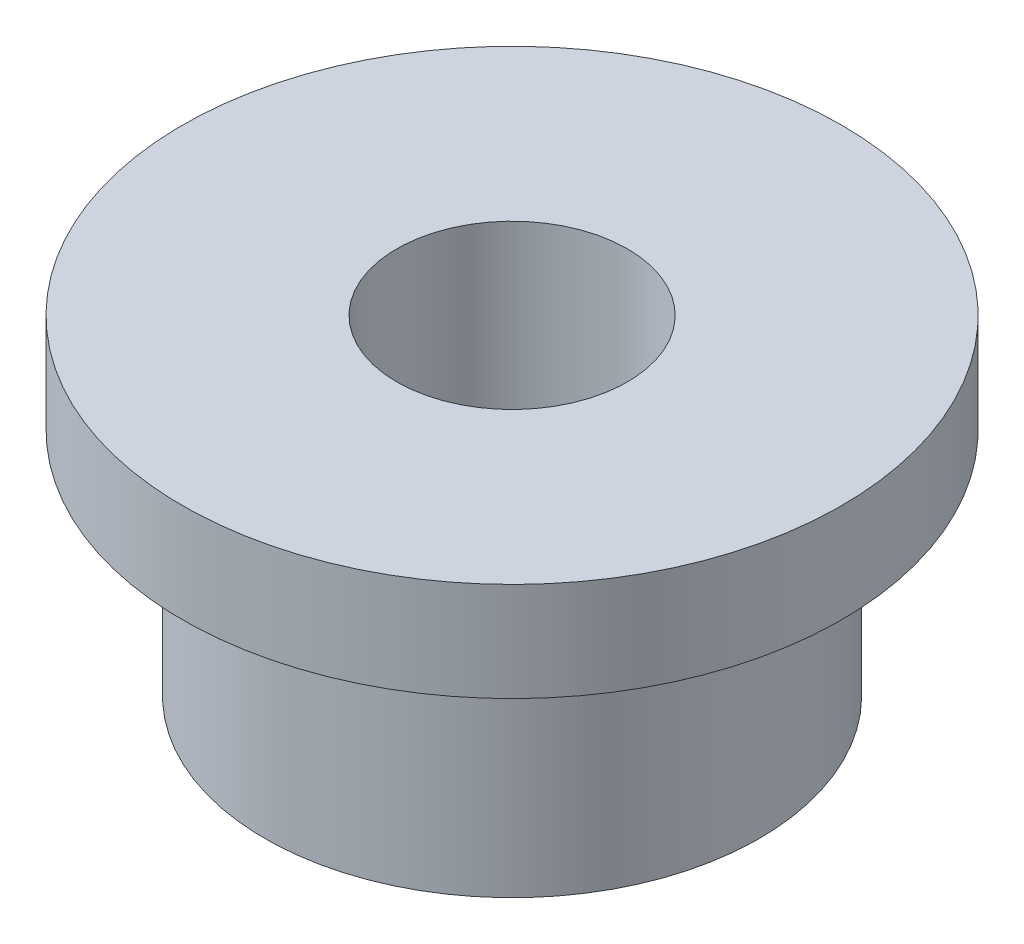
SolidWorks part; units mm, degrees
ref_plane "Front Plane" through (0, 0, 0) normal (0, 0, 1) x (1, 0, 0)
ref_plane "Top Plane" through (0, 0, 0) normal (0, 1, 0) x (1, 0, 0)
ref_plane "Right Plane" through (0, 0, 0) normal (1, 0, 0) x (0, 0, -1)
sketch "Sketch1" plane through (0, 0, 0) normal (0, 0, 1) x (1, 0, 0)
  line L0 (0, 0) -> (0, 10) construction
  line L1 (-7.5, 0) -> (7.5, 0) construction
  line L2 (7.5, 0) -> (7.5, 7)
  line L3 (-10, 10) -> (10, 10) construction
  line L4 (10, 10) -> (10, 7)
  line L5 (10, 7) -> (7.5, 7)
  line L7 (10, 10) -> (3.5, 10)
  line L8 (3.5, 10) -> (3.5, 0)
  line L9 (3.5, 0) -> (7.5, 0)
  line L10 (7.5, 0) -> (7.5, -0.0265)
  point P6 (0, 0)
  point P10 (0, 10)
  dimension "D1" = 15
  dimension "D2" = 7
  dimension "D3" = 10
  dimension "D4" = 20
  dimension "D5" = 3.5
revolve "Revolve1" add sketch "Sketch1" angle 360 about L0
cosmetic thread "Cosmetic Thread1" parameters "D1"=5, "D2"=11.797
